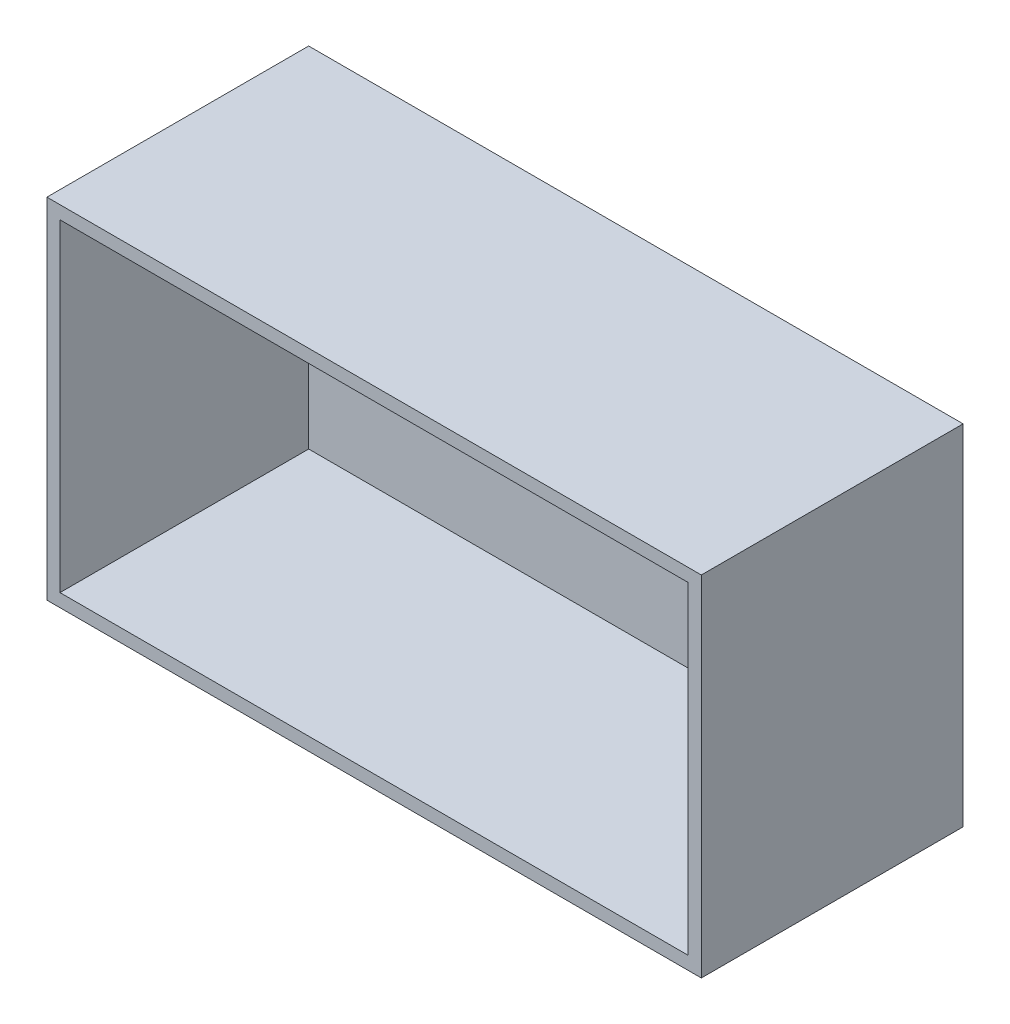
SolidWorks part; units mm, degrees
ref_plane "前基準面" through (0, 0, 0) normal (0, 0, 1) x (1, 0, 0)
ref_plane "上基準面" through (0, 0, 0) normal (0, 1, 0) x (1, 0, 0)
ref_plane "右基準面" through (0, 0, 0) normal (1, 0, 0) x (0, 0, -1)
sketch "草圖1" plane through (0, 0, 0) normal (0, 0, 1) x (1, 0, 0)
  line L1 (0, 0) -> (150, 0)
  line L2 (0, 0) -> (0, 80)
  line L3 (0, 80) -> (150, 80)
  line L4 (150, 0) -> (150, 80)
  dimension "D1" = 150
  dimension "D2" = 80
extrude "填料-伸長1" add sketch "草圖1" along normal blind 60
shell "薄殼1" thickness 3
